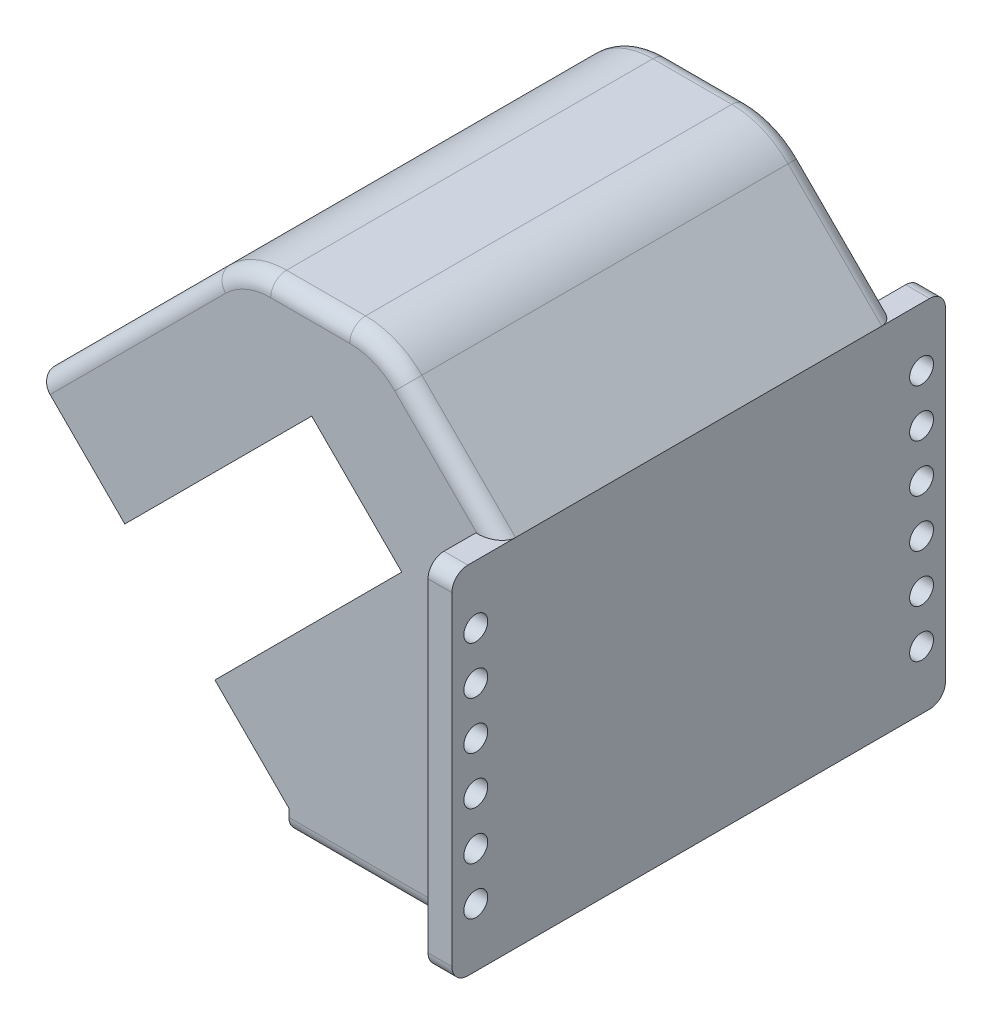
SolidWorks part; units mm, degrees
ref_plane "前视基准面" through (0, 0, 0) normal (0, 0, 1) x (1, 0, 0)
ref_plane "上视基准面" through (0, 0, 0) normal (0, 1, 0) x (1, 0, 0)
ref_plane "右视基准面" through (0, 0, 0) normal (1, 0, 0) x (0, 0, -1)
sketch "草图1" plane through (0, 0, 0) normal (0, 0, 1) x (1, 0, 0)
  line L5 (25.716, 61.2098) -> (43.9292, 61.2098)
  line L7 (32.1507, 1.8232) -> (58.6267, 1.8232)
  line L12 (58.6267, 46.5123) -> (58.6267, 1.8232)
  line L13 (25.716, 58.2098) -> (55.6267, 28.2991)
  line L14 (55.6267, 28.2991) -> (32.1507, 4.8232)
  line L17 (32.1507, 4.8232) -> (32.1507, 1.8232)
  line L18 (25.716, 58.2098) -> (25.716, 61.2098)
  line L19 (43.9292, 61.2098) -> (58.6267, 46.5123)
  line L20 (36.3226, 68.8164) -> (66.2333, 38.9057) construction
  dimension "D1" = 15
  dimension "D2" = 42.3
  dimension "D3" = 3
  dimension "D4" = 3
  dimension "D5" = 3
  dimension "D6" = 45
extrude "凸台-拉伸1" add sketch "草图1" along normal blind 50
sketch "草图3" plane through (41.9629, 41.9629, 0) normal (-0.7071, -0.7071, 0) x (0, 0, 1)
  line L0 (50, -19.3235) -> (46.15, -19.3235)
  line L1 (50, 22.9765) -> (50, -19.3235)
  line L2 (50, 22.9765) -> (46.15, 22.9765)
  line L3 (0, 22.9765) -> (0, -19.3235)
  line L4 (3.85, 19.9765) -> (3.85, -16.3235)
  line L5 (46.15, 19.9765) -> (46.15, -16.3235)
  line L6 (3.85, 22.9765) -> (0, 22.9765)
  line L7 (3.85, -19.3235) -> (0, -19.3235)
  line L8 (3.85, 19.9765) -> (6.85, 22.9765)
  line L9 (6.85, 22.9765) -> (3.85, 22.9765)
  line L10 (-6.5065, 1.8265) -> (10.2722, 1.8265) construction
  line L11 (6.85, -19.3235) -> (3.85, -19.3235)
  line L12 (3.85, -16.3235) -> (6.85, -19.3235)
  line L13 (25, 22.9765) -> (25, 16.7337) construction
  line L14 (43.15, -19.3235) -> (46.15, -19.3235)
  line L15 (46.15, -16.3235) -> (43.15, -19.3235)
  line L16 (43.15, 22.9765) -> (46.15, 22.9765)
  line L17 (46.15, 19.9765) -> (43.15, 22.9765)
  point P0 (0, 22.9765)
  dimension "D1" = 42.3
  dimension "D2" = 3
  dimension "D3" = 45
extrude "凸台-拉伸3" add sketch "草图3" along normal up to vertex (33.2 mm away) up to point (32.1507, 4.8232, 0)
sketch "草图4" plane through (18.487, 18.487, 0) normal (-0.7071, -0.7071, 0) x (0, 0, 1)
  line L1 (0, 25.0978) -> (50, 25.0978)
  line L2 (0, 25.0978) -> (0, 22.9765)
  line L3 (0, 22.9765) -> (50, 22.9765)
  line L4 (50, 25.0978) -> (50, 22.9765)
extrude "凸台-拉伸4" add sketch "草图4" against normal up to vertex
sketch "草图5" plane through (0, 0, 0) normal (0, 0, -1) x (-1, 0, 0)
  line L0 (-35.0145, 48.9113) -> (-46.3282, 37.5976)
  line L1 (-46.3282, 37.5976) -> (-22.8523, 14.1217)
  line L2 (-0.7401, 36.2338) -> (-32.1507, 4.8232) construction
  line L3 (-22.8523, 14.1217) -> (-11.5386, 25.4354)
  line L4 (-11.5386, 25.4354) -> (-35.0145, 48.9113)
  line L5 (-27.8374, 56.0884) -> (-53.5053, 30.4205) construction
extrude "切除-拉伸1" cut sketch "草图5" against normal through all
sketch "草图8" plane through (58.6267, 0, 0) normal (1, 0, 0) x (0, 0, -1)
  line L5 (-56, 46.5123) -> (6, 46.5123)
  line L7 (-25, 64.5937) -> (-25, -13.8029) construction
  line L8 (6, -4.1768) -> (6, 52.5123)
  line L9 (6, 52.5123) -> (-56, 52.5123)
  line L10 (-56, 52.5123) -> (-56, -4.1768)
  line L11 (-56, -4.1768) -> (6, -4.1768)
  line L12 (6, 1.8232) -> (6, 46.5123)
  line L14 (-56, 46.5123) -> (-56, 1.8232)
  line L16 (-56, 1.8232) -> (6, 1.8232)
  circle A0 centre (-53, 39.1623) radius 1.5
  circle A2 centre (-53, 33.1623) radius 1.5
  circle A3 centre (-53, 27.1623) radius 1.5
  circle A4 centre (-53, 21.1623) radius 1.5
  circle A5 centre (-53, 15.1623) radius 1.5
  circle A6 centre (-53, 9.1623) radius 1.5
  circle A7 centre (3, 9.1623) radius 1.5
  circle A8 centre (3, 15.1623) radius 1.5
  circle A9 centre (3, 21.1623) radius 1.5
  circle A10 centre (3, 27.1623) radius 1.5
  circle A11 centre (3, 33.1623) radius 1.5
  circle A12 centre (3, 39.1623) radius 1.5
  dimension "D2" = 3
  dimension "D3" = 3
  dimension "D4" = 6
  dimension "D5" = 7.35
  dimension "D1" = 6
extrude "凸台-拉伸5" add sketch "草图8" against normal blind 3
fillet "圆角1" radius 10 2 edges at (43.9292, 61.2098, 25) (25.716, 61.2098, 25)
fillet "圆角2" radius 2 16 edges at (52.7424, 52.3966, 0) (52.7424, 52.3966, 50) (43.6139, 60.4486, 50) (43.6139, 60.4486, 0) (34.8226, 61.2098, 50) (34.8226, 61.2098, 0) (26.0313, 60.4486, 50) (26.0313, 60.4486, 0) (11.7636, 47.2573, 0) (11.7636, 47.2573, 50) (43.8887, 1.8232, 50) (57.1267, 1.8232, 56) (43.8887, 1.8232, 0) (57.1267, 1.8232, -6) (57.1267, 46.5123, -6) (57.1267, 46.5123, 56)
